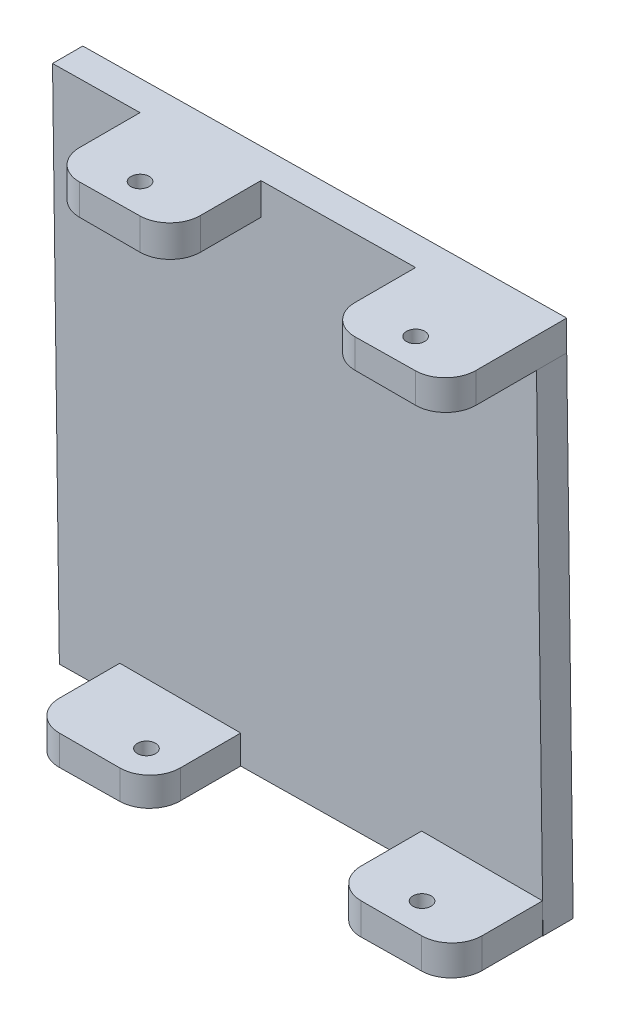
SolidWorks part; units mm, degrees
ref_plane "Front Plane" through (0, 0, 0) normal (0, 0, 1) x (1, 0, 0)
ref_plane "Top Plane" through (0, 0, 0) normal (0, 1, 0) x (1, 0, 0)
ref_plane "Right Plane" through (0, 0, 0) normal (1, 0, 0) x (0, 0, -1)
sketch "Sketch1" plane through (0, 0, 0) normal (0, 0, 1) x (1, 0, 0)
  line L0 (-47.0269, 0) -> (32.9731, 1.0576)
  line L1 (32.9731, 1.0576) -> (31.8428, 86.5576)
  line L2 (31.8428, 86.5576) -> (-48.1572, 85.5)
  line L3 (-48.1572, 85.5) -> (-47.0269, 0)
  dimension "D1" = 85.5
  dimension "D2" = 80
extrude "Boss-Extrude1" add sketch "Sketch1" along normal blind 5
sketch "Sketch2" plane through (0, 0, 0) normal (0, 0, 1) x (1, 0, 0)
  line L0 (-33.6818, 85.6914) -> (-33.6818, 80.6914)
  line L1 (31.8428, 86.5576) -> (-48.1572, 85.5) construction
  line L2 (-33.6818, 80.6914) -> (-13.6818, 80.6914)
  line L3 (-13.6818, 80.6914) -> (-13.6818, 85.9558)
  line L4 (-13.6818, 85.9558) -> (-33.6818, 85.6914)
  line L5 (-48.1572, 85.5) -> (-47.0269, 0) construction
  line L7 (11.9089, 86.2941) -> (11.9089, 81.5584)
  line L8 (11.9089, 81.5584) -> (31.9089, 81.5584)
  line L9 (31.9089, 81.5584) -> (31.9089, 86.5584)
  line L10 (32.9731, 1.0576) -> (31.8428, 86.5576) construction
  line L12 (31.9089, 86.5584) -> (11.9089, 86.2941)
  line L13 (-37.0278, 0.1322) -> (-37.0278, 5.1322)
  line L14 (-47.0269, 0) -> (32.9731, 1.0576) construction
  line L15 (-37.0278, 5.1322) -> (-17.0278, 5.1322)
  line L16 (-17.0278, 5.1322) -> (-17.0278, 0.3966)
  line L17 (-17.0278, 0.3966) -> (-37.0278, 0.1322)
  line L18 (12.907, 0.7923) -> (12.907, 6.0567)
  line L19 (12.907, 6.0567) -> (32.907, 6.0567)
  line L20 (32.907, 6.0567) -> (32.907, 1.0567)
  line L21 (32.907, 1.0567) -> (12.907, 0.7923)
  point P22 (0, 0)
  dimension "D1" = 5
  dimension "D2" = 20
  dimension "D3" = 5
  dimension "D4" = 20
  dimension "D5" = 0
  dimension "D7" = 5
  dimension "D8" = 5
  dimension "D9" = 20
  dimension "D10" = 0
  dimension "D11" = 10
  dimension "D12" = 20
extrude "Boss-Extrude2" add sketch "Sketch2" along normal blind 20
fillet "Fillet1" radius 5 8 edges at (32.907, 3.5567, 20) (12.907, 3.4245, 20) (-17.0278, 2.7644, 20) (-37.0278, 2.6322, 20) (31.9089, 84.0584, 20) (11.9089, 83.9262, 20) (-13.6818, 83.3236, 20) (-33.6818, 83.1914, 20)
sketch "Sketch5" plane through (-1.1385, 86.1216, 0) normal (-0.0132, 0.9999, 0) x (0.9999, 0.0132, 0)
  line L0 (-32.5462, -15) -> (-32.5462, -5) construction
  line L1 (-32.5462, -5) -> (-47.0228, -5) construction
  line L2 (33.0503, -5) -> (32.9842, -5) construction
  line L3 (13.0485, -15) -> (13.0485, -5) construction
  point P0 (-22.5462, -15)
  point P1 (23.0485, -15)
  point P12 (0, 0)
  point P13 (0, 0)
  dimension "D1" = 10
  dimension "D2" = 10
  dimension "D3" = 10
  dimension "D4" = 10
  dimension "D5" = 45.5947
hole_wizard "Ø3.0mm Dowel Hole1" positions "Sketch5" profile "Sketch7" hole size "Ø3.0" standard "ANSI Metric" end condition through all
sketch "Sketch7" plane through (-23.6827, 85.8235, 15) normal (0, 0, 1) x (-0.9999, -0.0132, 0)
  line L0 (0, 0) -> (0, 86.5649)
  line L1 (0, 86.5649) -> (1.5, 86.5649)
  line L2 (1.5, 86.5649) -> (1.5, 0)
  line L5 (1.5, 0) -> (0, 0)
  line L11 (0, -6.35) -> (0, 107.95) construction
  dimension "Thru Hole Dia." = 3
  dimension "Thru Hole Depth" = 86.5649
